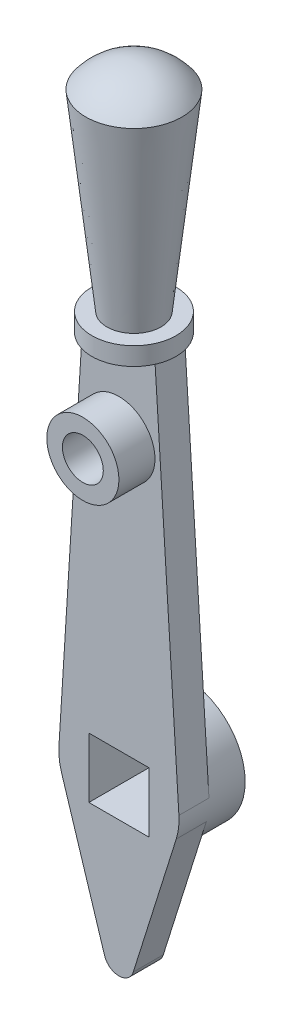
SolidWorks part; units mm, degrees
ref_plane "Front Plane" through (0, 0, 0) normal (0, 0, 1) x (1, 0, 0)
ref_plane "Top Plane" through (0, 0, 0) normal (0, 1, 0) x (1, 0, 0)
ref_plane "Right Plane" through (0, 0, 0) normal (1, 0, 0) x (0, 0, -1)
sketch "Sketch2" plane through (0, 0, 0) normal (0, 0, 1) x (1, 0, 0)
  line L0 (-9.5394, -3) -> (-2.3848, -25.75)
  line L2 (-2.3848, -25.75) -> (-0.9641, -30.2678) construction
  line L3 (0, 0) -> (0, -25) construction
  line L4 (9.5394, -3) -> (2.3848, -25.75)
  line L5 (6, 64) -> (-6, 64)
  line L6 (-6, 64) -> (-9.9803, 0.6268)
  line L7 (0, 0) -> (0, 77.4693) construction
  line L8 (6, 64) -> (9.9803, 0.6268)
  arc A0 (9.5394, -3) -> (9.9803, 0.6268) centre (0, 0) ccw
  arc A1 (-2.3848, -25.75) -> (2.3848, -25.75) centre (0, -25) ccw
  arc A2 (-9.5394, -3) -> (0, -10) centre (0, 0) ccw construction
  arc A3 (0, -10) -> (9.5394, -3) centre (0, 0) ccw construction
  arc A4 (2.3848, -25.75) -> (0, -22.5) centre (0, -25) ccw construction
  arc A5 (0, -22.5) -> (-2.3848, -25.75) centre (0, -25) ccw construction
  arc A6 (0, 10) -> (-9.9803, 0.6268) centre (0, 0) ccw construction
  arc A7 (-9.9803, 0.6268) -> (-9.5394, -3) centre (0, 0) ccw
  arc A8 (9.9803, 0.6268) -> (0, 10) centre (0, 0) ccw construction
  point P17 (0, 64)
  dimension "D1" = 20
  dimension "D2" = 2.5
  dimension "D3" = 25
  dimension "D4" = 64
  dimension "D5" = 12
extrude "Boss-Extrude1" add sketch "Sketch2" along normal mid plane 5
sketch "Sketch3" plane through (0, 0, 2.5) normal (0, 0, 1) x (1, 0, 0)
  circle A0 centre (0, 0) radius 10
  dimension "D1" = 20
extrude "Boss-Extrude2" add sketch "Sketch3" against normal blind 11
sketch "Sketch4" plane through (0, 0, 2.5) normal (0, 0, 1) x (1, 0, 0)
  circle A0 centre (0, 50) radius 6
  dimension "D1" = 12
  dimension "D2" = 50
extrude "Boss-Extrude3" add sketch "Sketch4" along normal blind 6
hole_wizard "M8 Tapped Hole1" positions "Sketch5" profile "Sketch6" tap size "M8" standard "ISO" end condition through all
sketch "Sketch5" plane through (0, 0, 8.5) normal (0, 0, 1) x (1, 0, 0)
  point P0 (0, 50)
sketch "Sketch6" plane through (0, 50, 8.5) normal (1, 0, 0) x (0, -1, 0)
  line L0 (0, 0) -> (0, 17)
  line L1 (0, 17) -> (3.4, 17)
  line L2 (3.4, 17) -> (3.4, 0)
  line L5 (3.4, 0) -> (0, 0)
  line L11 (0, -6.35) -> (0, 107.95) construction
  dimension "Thru Tap Drill Dia." = 6.8
  dimension "Thru Tap Drill Depth" = 17
cosmetic thread "Hole Thread1" parameters "D2"=8
sketch "Sketch7" plane through (0, 0, -8.5) normal (0, 0, -1) x (-1, 0, 0)
  line L1 (5, 5) -> (-5, 5)
  line L2 (5, 5) -> (5, -5)
  line L3 (5, -5) -> (-5, -5)
  line L4 (-5, 5) -> (-5, -5)
  line L5 (5, 5) -> (-5, -5) construction
  line L6 (5, -5) -> (-5, 5) construction
  point P0 (0, 0)
  dimension "D1" = 10
extrude "Cut-Extrude1" cut sketch "Sketch7" against normal through all
sketch "Sketch8" plane through (0, 0, 0) normal (0, 0, 1) x (1, 0, 0)
  line L0 (0, 0) -> (0, 120.1429) construction
  line L1 (0, 64) -> (-7, 64)
  line L3 (-7, 67) -> (-4.5, 67)
  line L4 (-4.5, 67) -> (-8, 99)
  line L5 (0, 103) -> (0, 64)
  line L6 (-7, 67) -> (-7, 64)
  line L7 (6, 64) -> (-6, 64) construction
  arc A0 (-8, 99) -> (0, 103) centre (0, 93) cw
  dimension "D1" = 16
  dimension "D6" = 10
  dimension "D2" = 9
  dimension "D3" = 3
  dimension "D4" = 14
  dimension "D5" = 32
revolve "Revolve1" add sketch "Sketch8" angle 360 about L0
